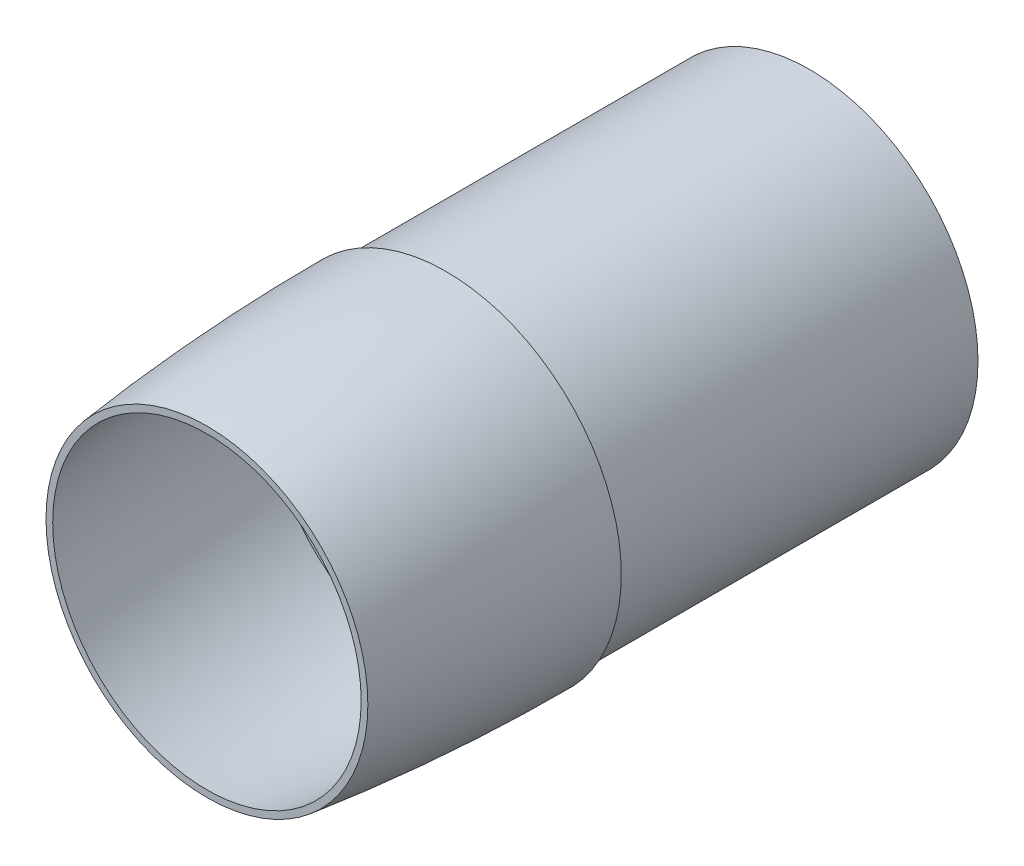
SolidWorks part; units mm, degrees
ref_plane "Front Plane" through (0, 0, 0) normal (0, 0, 1) x (1, 0, 0)
ref_plane "Top Plane" through (0, 0, 0) normal (0, 1, 0) x (1, 0, 0)
ref_plane "Right Plane" through (0, 0, 0) normal (1, 0, 0) x (0, 0, -1)
sketch "Sketch1" plane through (0, 0, 0) normal (1, 0, 0) x (0, 0, -1)
  line L0 (0, 0) -> (0, 419.7439) construction
  line L1 (-182.6049, 419.7439) -> (0, 419.7439) construction
  line L2 (0, 459.2439) -> (0, 457.7439)
  line L3 (0, 457.7439) -> (82, 457.7439)
  line L4 (82, 457.7439) -> (82, 419.7439)
  line L5 (0, 457.7439) -> (0, 459.2439) construction
  line L6 (79, 454.7439) -> (79, 419.7439)
  line L7 (-3, 454.7439) -> (79, 454.7439)
  line L8 (-3, 457.7341) -> (-3, 454.7439)
  line L10 (79, 419.7439) -> (82, 419.7439)
  line L11 (-182.6049, 419.7439) -> (82, 419.7439)
  line L12 (-54, 454.5476) -> (-54, 456.0581)
  line L13 (0, 460.7439) -> (0, 457.7439) construction
  arc A1 (-3, 457.7341) -> (-54, 454.5476) centre (0, 0) ccw
  arc A2 (-3, 457.7341) -> (-188.7629, 417.0109) centre (0, 0) ccw construction
  arc A3 (0, 459.2439) -> (-54, 456.0581) centre (0, 0) ccw
  arc A5 (0, 460.7439) -> (-190, 419.7439) centre (0, 0) ccw construction
  dimension "D4" = 82
  dimension "D5" = 38
  dimension "D6" = 3
revolve "Revolve1" add sketch "Sketch1" angle 360 about L1
